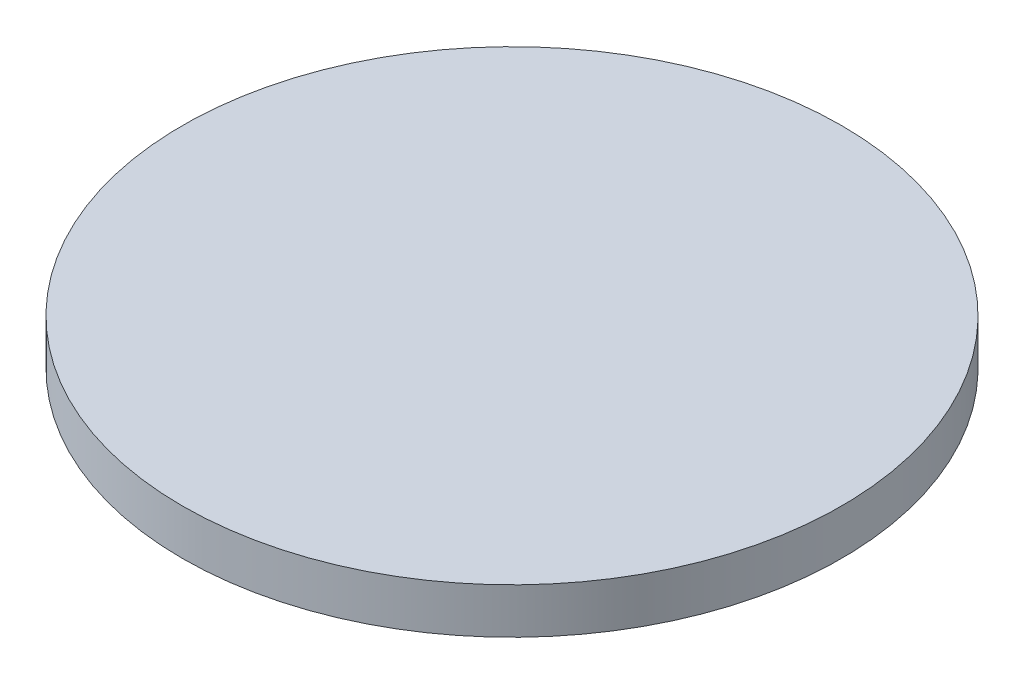
SolidWorks part; units mm, degrees
material "6061-T6 (SS)"
ref_plane "Front Plane" through (0, 0, 0) normal (0, 0, 1) x (1, 0, 0)
ref_plane "Top Plane" through (0, 0, 0) normal (0, 1, 0) x (1, 0, 0)
ref_plane "Right Plane" through (0, 0, 0) normal (1, 0, 0) x (0, 0, -1)
sketch "Sketch1" plane through (0, 0, 0) normal (0, 1, 0) x (1, 0, 0)
  line L5 (0, 0) -> (127.635, 0)
  line L6 (0, 0) -> (0, 127.635)
  line L7 (0, 127.635) -> (127.635, 127.635)
  line L8 (127.635, 0) -> (127.635, 127.635)
  dimension "D1" = 127.635
  dimension "D2" = 127.635
extrude "Boss-Extrude1" add sketch "Sketch1" along normal blind 9.525 contours L5 L8 L7 L6
sketch "Sketch13" plane through (0, 9.525, 0) normal (0, 1, 0) x (1, 0, 0)
  circle A0 centre (63.8175, 63.8175) radius 92.075
  dimension "D1" = 184.15
extrude "Boss-Extrude2" add sketch "Sketch13" against normal blind 12.7 contours A0
sketch "Sketch6" [suppressed] plane through (127.635, 0, 0) normal (1, 0, 0) x (0, 0, -1)
  circle A0 centre (4.7625, 4.7625) radius 1.3526
  dimension "D1" = 2.7051
extrude "6-32 hole1" [suppressed] cut sketch "Sketch6" against normal blind 12.7
sketch "Sketch7" [suppressed] plane through (0, 0, -127.635) normal (0, 0, -1) x (-1, 0, 0)
  circle A0 centre (-122.8725, 4.7625) radius 1.3525
  dimension "D1" = 2.7051
sketch "Sketch8" [suppressed] plane through (0, 0, 0) normal (-1, 0, 0) x (0, 0, 1)
  circle A0 centre (-122.8725, 4.7625) radius 1.3525
  dimension "D1" = 2.7051
sketch "Sketch9" [suppressed] plane through (0, 0, 0) normal (0, 0, 1) x (1, 0, 0)
  circle A0 centre (4.7625, 4.7625) radius 1.3526
  dimension "D1" = 2.7051
sketch "Sketch5" plane through (0, 9.525, 0) normal (0, 1, 0) x (1, 0, 0)
  circle A0 centre (63.8175, 63.8175) radius 46.355
  circle A1 centre (63.8175, 63.8175) radius 92.075 construction
  dimension "D1" = 92.71
extrude "Cut-Extrude1" [suppressed] cut sketch "Sketch5" against normal blind 9.525
sketch "Sketch11" [suppressed] plane through (0, 9.525, 0) normal (0, 1, 0) x (1, 0, 0)
  line L0 (63.8175, 63.8175) -> (63.8175, 115.443) construction
  circle A0 centre (63.8175, 115.443) radius 1.4351
  dimension "D2" = 2.8702
  dimension "D1" = 51.6255
extrude "Cut-Extrude3" [suppressed] cut sketch "Sketch11" against normal through all contours A0
pattern_circular "CirPattern1" [suppressed] count 12 over 360
sketch "Sketch12" [suppressed] plane through (0, 9.525, 0) normal (0, 1, 0) x (1, 0, 0)
  circle A0 centre (63.8175, 63.8175) radius 56.4198
  dimension "D1" = 112.8395
extrude "Cut-Extrude4" [suppressed] cut sketch "Sketch12" against normal blind 1.27
sketch "Sketch15" [suppressed] plane through (0, 9.525, 0) normal (0, 1, 0) x (1, 0, 0)
  line L0 (63.8175, 63.8175) -> (-29.845, 63.8175) construction
  line L1 (0, -39.1057) -> (0, 39.1057) construction
  line L2 (-20.0025, 63.8175) -> (-25.0825, 63.8175)
  line L3 (-8.7458, 105.7742) -> (-13.2051, 108.2104)
  line L4 (-8.7458, 105.7742) -> (-20.0025, 63.8175) construction
  circle A0 centre (63.8175, 63.8175) radius 56.4198 construction
  arc A1 (-20.0025, 63.8175) -> (-8.7458, 105.7742) centre (63.8175, 63.8175) cw
  arc A2 (-25.0825, 63.8175) -> (-13.2051, 108.2104) centre (63.8175, 63.8175) cw
  circle A3 centre (63.8175, 63.8175) radius 93.6625 construction
  point P0 (63.8175, 63.8175)
  point P11 (-14.3741, 84.7959)
  dimension "D1" = 46.482
  dimension "D2" = 88.9
  dimension "D3" = 83.82
  dimension "D4" = 43.942
sketch "Sketch16" plane through (0, 9.525, 0) normal (0, 1, 0) x (1, 0, 0)
  circle A0 centre (63.8175, 63.8175) radius 88.9
  circle A1 centre (63.8175, 63.8175) radius 85.725
  dimension "D1" = 177.8
  dimension "D2" = 171.45
extrude "Cut-Extrude5" [suppressed] cut sketch "Sketch16" against normal blind 7.62
sketch "Sketch18" [suppressed] plane through (0, 8.255, 0) normal (0, 1, 0) x (1, 0, 0)
  line L0 (63.8175, 185.7252) -> (63.8175, -48.6103) construction
ref_plane "Plane1" [suppressed] through (63.8175, 0, 0) normal (-1, 0, 0) x (0, 0, 1)
ref_plane "Plane2" [suppressed] through (0, 0, 29.845) normal (0, 0, 1) x (1, 0, 0)
sketch "Sketch17" [suppressed] plane through (0, 0, 29.845) normal (0, 0, 1) x (1, 0, 0)
  line L0 (63.8175, 103.0287) -> (63.8175, -103.0287) construction
  line L1 (157.48, 9.525) -> (-29.845, 9.525) construction
  circle A0 centre (63.8175, 5.715) radius 1.4351
  dimension "D1" = 2.8702
  dimension "D2" = 3.81
extrude "Cut-Extrude6" [suppressed] cut sketch "Sketch17" against normal blind 15.24
pattern_circular "CirPattern2" [suppressed] count 12 over 360
sketch "Sketch19" plane through (0, -3.175, 0) normal (0, -1, 0) x (1, 0, 0)
  circle A0 centre (63.8175, -63.8175) radius 25.4
  dimension "D1" = 50.8
extrude "Cut-Extrude7" [suppressed] cut sketch "Sketch19" against normal blind 87.63
